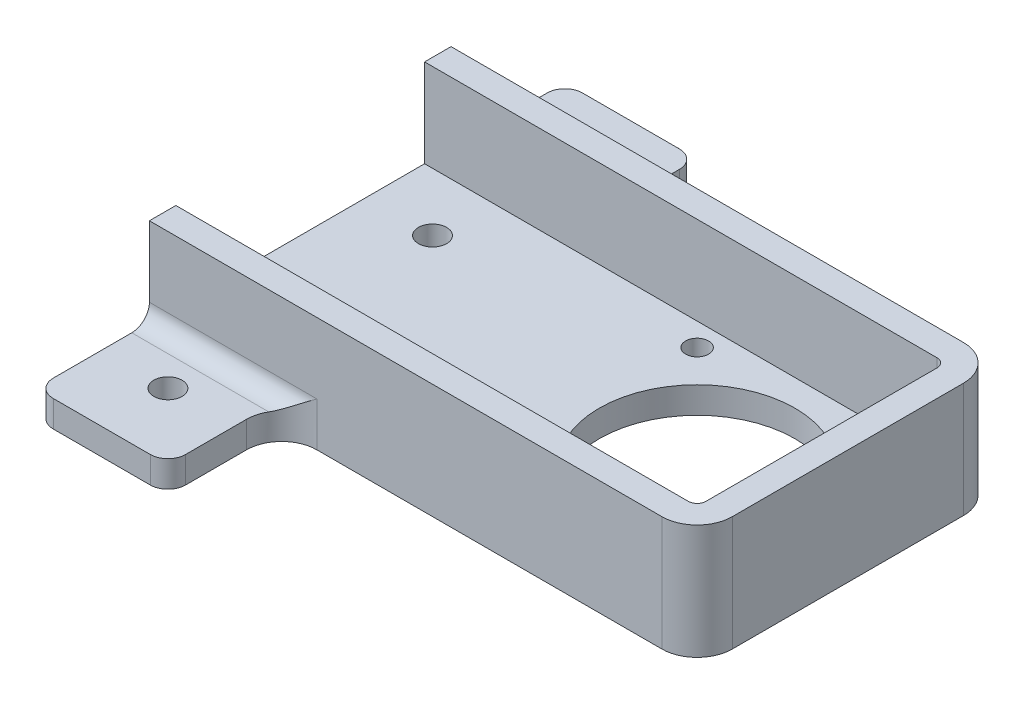
SolidWorks part; units mm, degrees
ref_plane "Front Plane" through (0, 0, 0) normal (0, 0, 1) x (1, 0, 0)
ref_plane "Top Plane" through (0, 0, 0) normal (0, 1, 0) x (1, 0, 0)
ref_plane "Right Plane" through (0, 0, 0) normal (1, 0, 0) x (0, 0, -1)
sketch "Sketch1" plane through (0, 0, 0) normal (0, 1, 0) x (1, 0, 0)
  line L0 (0, 0) -> (15, 0)
  line L2 (62.1, 12.9) -> (62.1, 47.1)
  line L4 (15, 60) -> (0, 60)
  line L5 (0, 60) -> (0, 0)
  line L6 (62.1, 47.1) -> (15, 47.1)
  line L7 (15, 47.1) -> (15, 60)
  line L8 (62.1, 12.9) -> (15, 12.9)
  line L9 (15, 12.9) -> (15, 0)
  point P9 (62.1, 30)
  point P10 (0, 30)
  dimension "D1" = 62.1
  dimension "D2" = 15
  dimension "D3" = 60
  dimension "D4" = 34.2
extrude "Boss-Extrude1" add sketch "Sketch1" along normal blind 3
sketch "Sketch2" plane through (0, 3, 0) normal (0, 1, 0) x (1, 0, 0)
  line L0 (0, 60) -> (0, 0) construction
  line L1 (15, 60) -> (0, 60) construction
  line L2 (0, 0) -> (15, 0) construction
  circle A0 centre (7.5, 52.5) radius 1.6
  circle A1 centre (7.5, 37.5) radius 1.6
  circle A2 centre (7.5, 7.5) radius 1.6
  circle A3 centre (7.5, 22.5) radius 1.6
  dimension "D1" = 3.2
  dimension "D2" = 7.5
  dimension "D3" = 7.5
  dimension "D4" = 7.5
  dimension "D5" = 15
  dimension "D6" = 15
extrude "Cut-Extrude1" cut sketch "Sketch2" against normal through all
sketch "Sketch3" plane through (0, 3, 0) normal (0, 1, 0) x (1, 0, 0)
  line L0 (62.1, 12.9) -> (15, 12.9)
  line L1 (15, 12.9) -> (0, 12.9)
  line L2 (0, 60) -> (0, 0) construction
  line L3 (0, 12.9) -> (0, 15.9)
  line L4 (0, 15.9) -> (59.1, 15.9)
  line L5 (59.1, 15.9) -> (59.1, 44.1)
  line L6 (59.1, 44.1) -> (0, 44.1)
  line L7 (0, 44.1) -> (0, 47.1)
  line L8 (0, 47.1) -> (62.1, 47.1)
  line L9 (62.1, 47.1) -> (15, 47.1) construction
  line L10 (62.1, 12.9) -> (62.1, 47.1) construction
  line L11 (62.1, 47.1) -> (62.1, 12.9)
  dimension "D1" = 3
  dimension "D2" = 3
  dimension "D3" = 3
extrude "Boss-Extrude2" add sketch "Sketch3" along normal blind 10
sketch "Sketch5" plane through (0, 3, 0) normal (0, 1, 0) x (1, 0, 0)
  line L0 (59.1, 44.1) -> (59.1, 15.9) construction
  circle A0 centre (45, 30) radius 11.1
  point P5 (59.1, 30)
  dimension "D1" = 22.2
  dimension "D2" = 14.1
extrude "Cut-Extrude2" cut sketch "Sketch5" against normal up to next
sketch "Sketch6" plane through (0, 3, 0) normal (0, 1, 0) x (1, 0, 0)
  line L0 (45, 44.1) -> (45, 15.9) construction
  line L1 (0, 44.1) -> (59.1, 44.1) construction
  line L2 (59.1, 15.9) -> (0, 15.9) construction
  line L3 (59.1, 44.1) -> (59.1, 15.9) construction
  line L4 (59.1, 30) -> (27.5371, 30) construction
  circle A0 centre (56.5, 41.5) radius 1.3
  circle A1 centre (33.5, 41.5) radius 1.3
  circle A2 centre (33.5, 18.5) radius 1.3
  circle A3 centre (56.5, 18.5) radius 1.3
  dimension "D2" = 2.6
  dimension "D1" = 14.1
  dimension "D3" = 23
  dimension "D4" = 23
extrude "Cut-Extrude3" cut sketch "Sketch6" against normal up to next
fillet "Fillet1" radius 1 2 edges at (59.1, 8, -15.9) (59.1, 8, -44.1)
fillet "Fillet2" radius 4 2 edges at (62.1, 6.5, -12.9) (62.1, 6.5, -47.1)
fillet "Fillet3" radius 4 2 edges at (15, 1.5, -47.1) (15, 1.5, -12.9)
fillet "Fillet4" radius 2 2 edges at (9.5, 3, -12.9) (9.5, 3, -47.1)
fillet "Fillet5" radius 2 4 edges at (0, 1.5, -60) (15, 1.5, -60) (0, 1.5, 0) (15, 1.5, 0)
